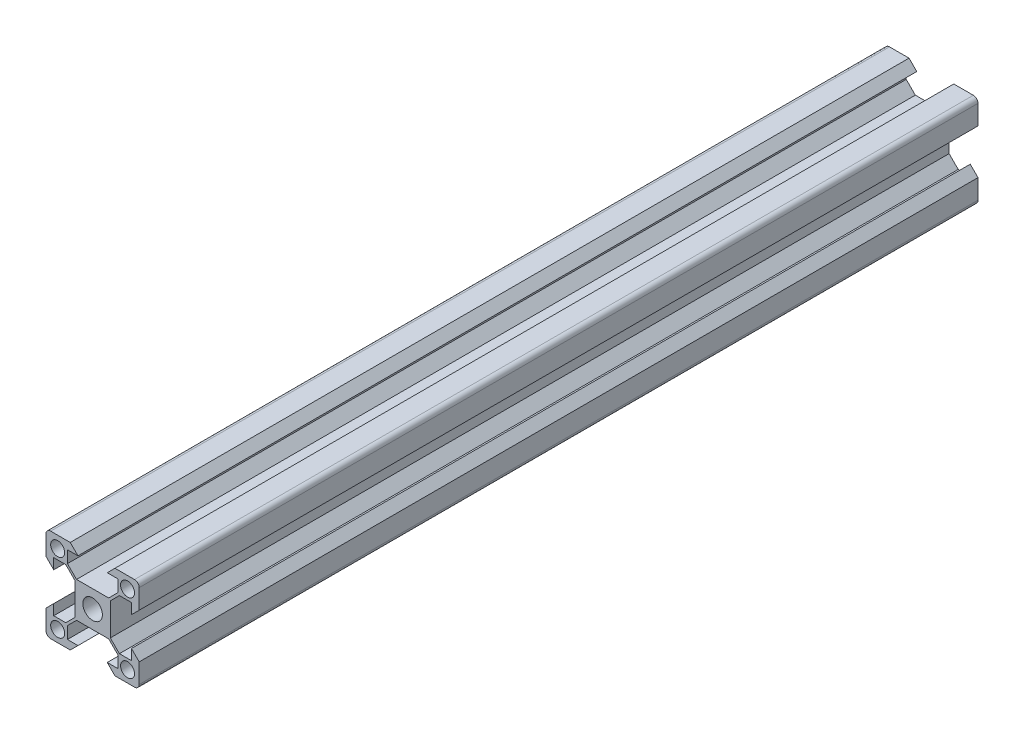
SolidWorks part; units mm, degrees
material "铝管"
ref_plane "前视基准面" through (0, 0, 0) normal (0, 0, 1) x (1, 0, 0)
ref_plane "上视基准面" through (0, 0, 0) normal (0, 1, 0) x (1, 0, 0)
ref_plane "右视基准面" through (0, 0, 0) normal (1, 0, 0) x (0, 0, -1)
sketch "草图1" plane through (0, 0, 0) normal (0, 0, 1) x (1, 0, 0)
  line L0 (0, 0) -> (-40.5659, 40.5659) construction
  line L1 (0, 0) -> (0, 75.5033) construction
  line L2 (-10, 10) -> (-10, 4.8)
  line L3 (-10, 4.8) -> (-8.34, 3.14)
  line L4 (-8.34, 3.14) -> (-8.34, 5.4)
  line L5 (-5.7536, 5.4) -> (-3.8, 3.4464)
  line L6 (-3.8, 3.4464) -> (-3.8, -3.4464)
  line L7 (-3.8, 0) -> (15.6715, 0) construction
  line L8 (-5.4, 8.34) -> (-5.4, 5.7536)
  line L9 (-3.4464, 3.8) -> (3.4464, 3.8)
  line L10 (-5.4, 5.7536) -> (-3.4464, 3.8)
  line L11 (-3.14, 8.34) -> (-5.4, 8.34)
  line L12 (-8.34, 5.4) -> (-5.7536, 5.4)
  line L13 (-4.8, 10) -> (-3.14, 8.34)
  line L14 (-10, 10) -> (-4.8, 10)
  line L15 (-10, -10) -> (-4.8, -10)
  line L16 (-4.8, -10) -> (-3.14, -8.34)
  line L17 (-8.34, -5.4) -> (-5.7536, -5.4)
  line L18 (-3.14, -8.34) -> (-5.4, -8.34)
  line L19 (-5.4, -5.7536) -> (-3.4464, -3.8)
  line L20 (-3.4464, -3.8) -> (3.4464, -3.8)
  line L21 (-5.4, -8.34) -> (-5.4, -5.7536)
  line L22 (-5.7536, -5.4) -> (-3.8, -3.4464)
  line L23 (-8.34, -3.14) -> (-8.34, -5.4)
  line L24 (-10, -4.8) -> (-8.34, -3.14)
  line L25 (-10, -10) -> (-10, -4.8)
  line L26 (10, -10) -> (10, -4.8)
  line L27 (10, -4.8) -> (8.34, -3.14)
  line L28 (8.34, -3.14) -> (8.34, -5.4)
  line L29 (5.7536, -5.4) -> (3.8, -3.4464)
  line L30 (5.4, -8.34) -> (5.4, -5.7536)
  line L31 (5.4, -5.7536) -> (3.4464, -3.8)
  line L32 (3.14, -8.34) -> (5.4, -8.34)
  line L33 (8.34, -5.4) -> (5.7536, -5.4)
  line L34 (4.8, -10) -> (3.14, -8.34)
  line L35 (10, -10) -> (4.8, -10)
  line L36 (10, 10) -> (4.8, 10)
  line L37 (4.8, 10) -> (3.14, 8.34)
  line L38 (8.34, 5.4) -> (5.7536, 5.4)
  line L39 (3.14, 8.34) -> (5.4, 8.34)
  line L40 (5.4, 5.7536) -> (3.4464, 3.8)
  line L41 (5.4, 8.34) -> (5.4, 5.7536)
  line L42 (3.8, 3.4464) -> (3.8, -3.4464)
  line L43 (5.7536, 5.4) -> (3.8, 3.4464)
  line L44 (8.34, 3.14) -> (8.34, 5.4)
  line L45 (10, 4.8) -> (8.34, 3.14)
  line L46 (10, 10) -> (10, 4.8)
  circle A0 centre (-7.5, 7.5) radius 1.5
  circle A1 centre (0, 0) radius 2.1
  circle A2 centre (-7.5, -7.5) radius 1.5
  circle A3 centre (7.5, -7.5) radius 1.5
  circle A4 centre (7.5, 7.5) radius 1.5
  point P54 (0, -3.8)
  point P64 (0, 3.8)
  dimension "D6" = 3
  dimension "D7" = 7.5
  dimension "D9" = 4.2
  dimension "D1" = 45
  dimension "D2" = 4.8
  dimension "D3" = 3.8
  dimension "D4" = 10
  dimension "D5" = 5.4
  dimension "D8" = 3.14
  dimension "D10" = 10
  dimension "D11" = 0.5
extrude "凸台-拉伸1" add sketch "草图1" along normal mid plane 180
fillet "圆角1" radius 1 4 edges at (-10, -10, 0) (10, -10, 0) (-10, 10, 0) (10, 10, 0)
